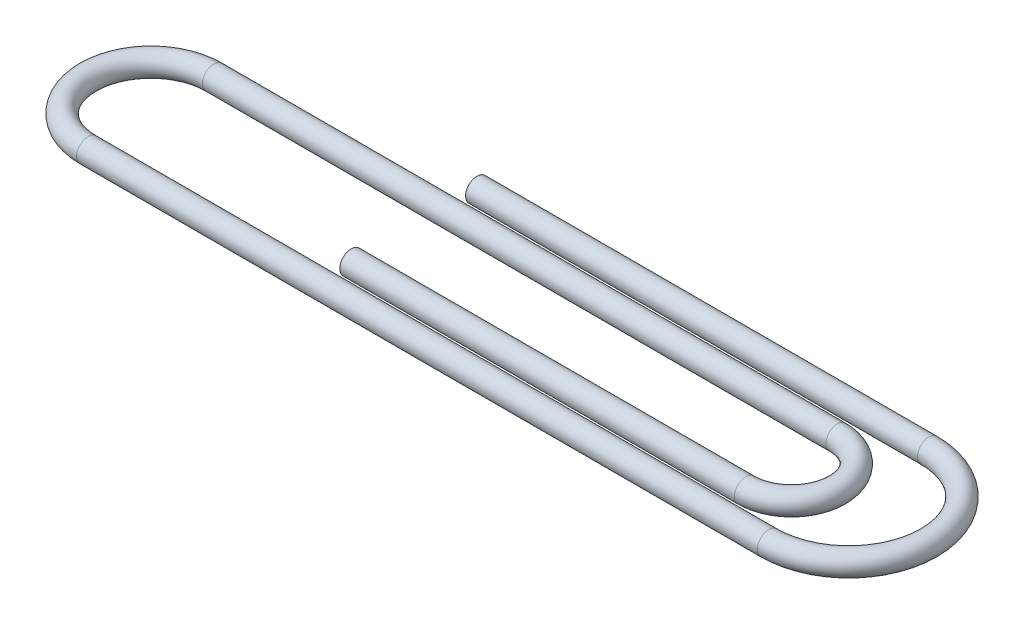
SolidWorks part; units mm, degrees
ref_plane "Front Plane" through (0, 0, 0) normal (0, 0, 1) x (1, 0, 0)
ref_plane "Top Plane" through (0, 0, 0) normal (0, 1, 0) x (1, 0, 0)
ref_plane "Right Plane" through (0, 0, 0) normal (1, 0, 0) x (0, 0, -1)
sketch "Sketch1" plane through (0, 0, 0) normal (0, 1, 0) x (1, 0, 0)
  line L0 (0, 0) -> (19.75, 0)
  line L1 (19.75, -7) -> (-10, -7)
  line L2 (-10, -1.5) -> (17.25, -1.5)
  line L3 (17.25, -5.5) -> (0, -5.5)
  arc A0 (19.75, 0) -> (19.75, -7) centre (19.75, -3.5) cw
  arc A1 (-10, -7) -> (-10, -1.5) centre (-10, -4.25) cw
  arc A2 (17.25, -1.5) -> (17.25, -5.5) centre (17.25, -3.5) cw
  point P11 (23.25, -3.5)
  point P13 (19.25, -3.5)
  point P15 (-12.75, -4.25)
  dimension "D1" = 3.5
  dimension "D4" = 32
  dimension "D6" = 4
  dimension "D2" = 10
  dimension "D3" = 1.5
  dimension "D5" = 1.5
sweep "Sweep1" add path "Sketch1" circular profile diameter 1 parameters "D3"=1
